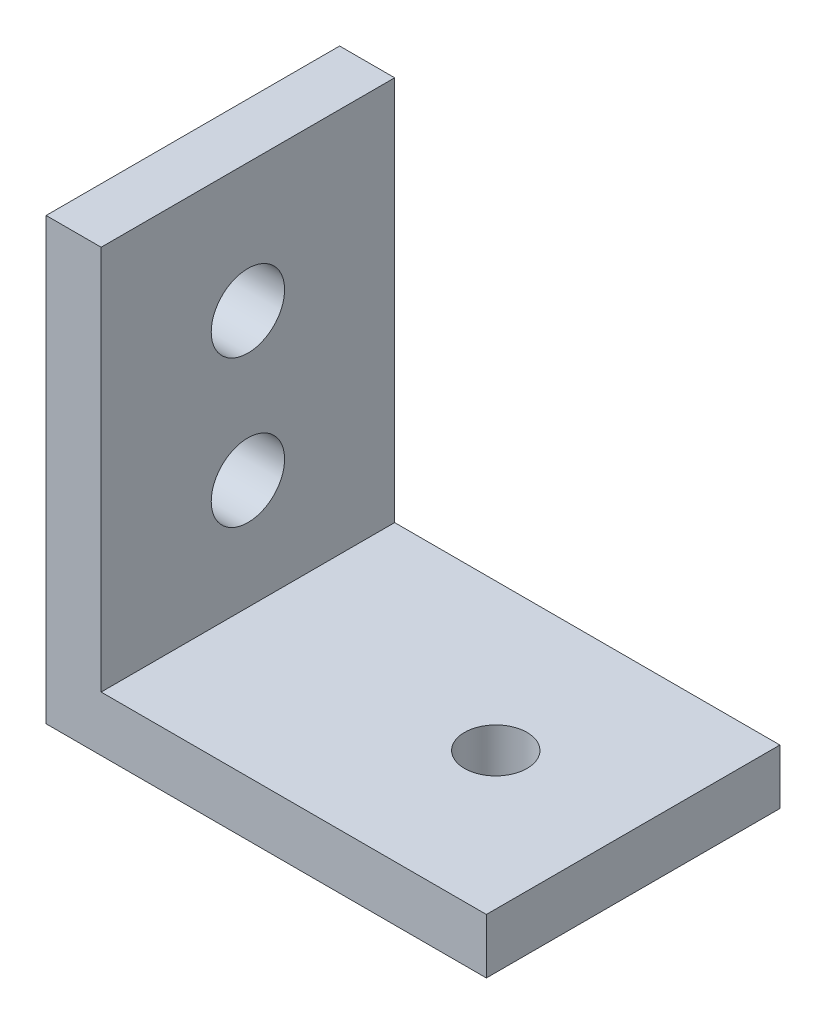
SolidWorks part; units mm, degrees
material "6061 Alloy"
ref_plane "Front Plane" through (0, 0, 0) normal (0, 0, 1) x (1, 0, 0)
ref_plane "Top Plane" through (0, 0, 0) normal (0, 1, 0) x (1, 0, 0)
ref_plane "Right Plane" through (0, 0, 0) normal (1, 0, 0) x (0, 0, -1)
sketch "Sketch1" plane through (0, 0, 0) normal (0, 0, 1) x (1, 0, 0)
  line L0 (-23.7711, 18.9433) -> (-23.7711, -19.1567)
  line L1 (-23.7711, -19.1567) -> (14.3289, -19.1567)
  line L2 (-19.0086, 18.9433) -> (-19.0086, -14.3942)
  line L3 (-19.0086, -14.3942) -> (14.3289, -14.3942)
  line L4 (-23.7711, 18.9433) -> (-19.0086, 18.9433)
  line L5 (14.3289, -14.3942) -> (14.3289, -19.1567)
  dimension "D1" = 38.1
  dimension "D2" = 38.1
  dimension "D3" = 4.7625
extrude "Boss-Extrude1" add sketch "Sketch1" along normal blind 25.4
sketch "Sketch2" plane through (-23.7711, 0, 0) normal (-1, 0, 0) x (0, 0, 1)
  circle A0 centre (12.7, 7.8308) radius 3.175
  circle A1 centre (12.7, -4.8692) radius 3.175
  circle A2 centre (12.7, -4.8692) radius 3.175 construction
  circle A3 centre (12.7, 7.8308) radius 3.175 construction
  dimension "D1" = 6.35
extrude "Cut-Extrude1" cut sketch "Sketch2" against normal up to next
hole_wizard "1/4-28 Tapped Hole1" positions "Sketch5" profile "Sketch4" tap size "1/4-28" standard "ANSI Inch" end condition up to next
sketch "Sketch5" plane through (0, -19.1567, 0) normal (0, -1, 0) x (-1, 0, 0)
  line L0 (23.7711, -25.4) -> (-14.3289, -25.4) construction
  line L1 (23.7711, -25.4) -> (23.7711, 0) construction
  point P0 (-2.4417, -12.7)
  dimension "D1" = 12.7
  dimension "D2" = 26.2128
sketch "Sketch4" plane through (2.4417, -19.1567, 12.7) normal (1, 0, 0) x (0, 0, -1)
  line L0 (0, 0) -> (0, 4.7625)
  line L1 (0, 4.7625) -> (2.7051, 4.7625)
  line L2 (2.7051, 4.7625) -> (2.7051, 0)
  line L5 (2.7051, 0) -> (0, 0)
  line L11 (0, -6.35) -> (0, 107.95) construction
  dimension "Thru Tap Drill Dia." = 5.4102
  dimension "Thru Tap Drill Depth" = 4.7625
cosmetic thread "Hole Thread2" parameters "D1"=4.7625, "D2"=6.35
